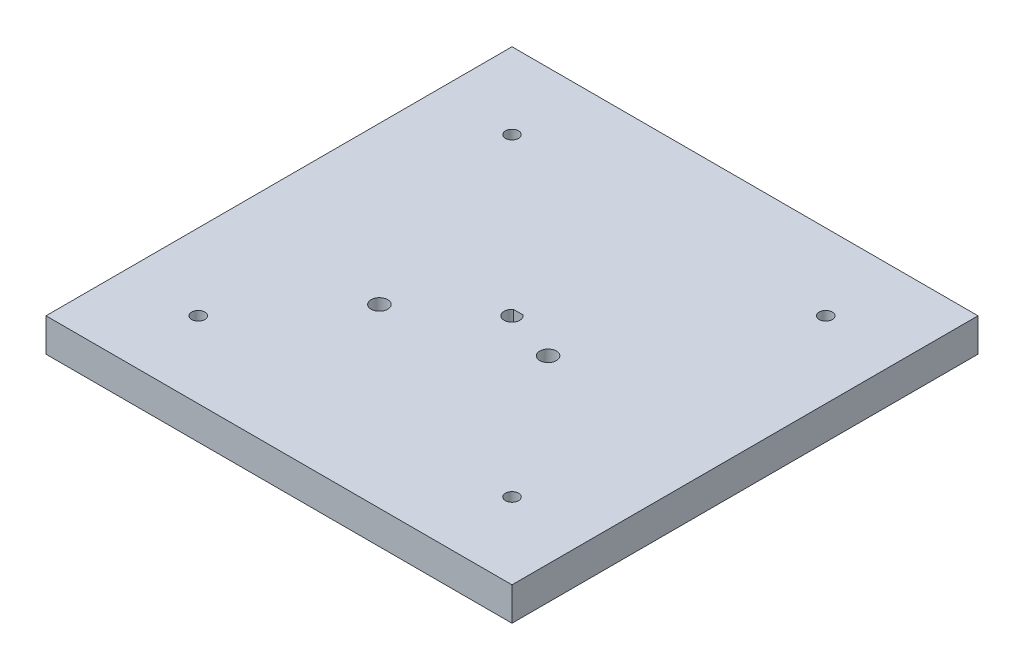
SolidWorks part; units mm, degrees
ref_plane "Front Plane" through (0, 0, 0) normal (0, 0, 1) x (1, 0, 0)
ref_plane "Top Plane" through (0, 0, 0) normal (0, 1, 0) x (1, 0, 0)
ref_plane "Right Plane" through (0, 0, 0) normal (1, 0, 0) x (0, 0, -1)
sketch "Sketch2" plane through (0, 0, 0) normal (0, 1, 0) x (1, 0, 0)
  line L0 (-1.8, 2.4) -> (1.8, 2.4)
  line L1 (-88.9, -88.9) -> (88.9, -88.9)
  line L2 (-88.9, -88.9) -> (-88.9, 88.9)
  line L3 (-88.9, 88.9) -> (88.9, 88.9)
  line L4 (88.9, -88.9) -> (88.9, 88.9)
  line L5 (-88.9, -88.9) -> (88.9, 88.9) construction
  line L6 (-88.9, 88.9) -> (88.9, -88.9) construction
  arc A1 (-1.8, 2.4) -> (1.8, 2.4) centre (0, 0) ccw
  arc A2 (1.8, 2.4) -> (-1.8, 2.4) centre (0, 0) ccw construction
  point P0 (0, 0)
  dimension "D3" = 6
  dimension "D1" = 177.8
  dimension "D2" = 177.8
  dimension "D4" = 2.4
extrude "Boss-Extrude1" add sketch "Sketch2" along normal mid plane 12.7
sketch "Sketch3" plane through (0, -6.35, 0) normal (0, -1, 0) x (1, 0, 0)
  circle A0 centre (-59.8566, -59.8566) radius 2.5 construction
  circle A1 centre (59.8566, -59.8566) radius 2.5 construction
  circle A2 centre (59.8566, 59.8566) radius 2.5 construction
  circle A3 centre (-59.8566, 59.8566) radius 2.5 construction
  circle A4 centre (-59.8566, -59.8566) radius 2.5
  circle A5 centre (59.8566, -59.8566) radius 2.5
  circle A6 centre (59.8566, 59.8566) radius 2.5
  circle A7 centre (-59.8566, 59.8566) radius 2.5
extrude "Cut-Extrude1" cut sketch "Sketch3" against normal up to surface (12.7 mm away) up to face at (0, 6.35, 0)
sketch "Sketch5" plane through (0, 6.35, 0) normal (0, 1, 0) x (1, 0, 0)
  circle A0 centre (20.1133, -6.35) radius 3.175 construction
  circle A1 centre (-29.0357, -21.5526) radius 3.175 construction
  circle A2 centre (20.1133, -6.35) radius 3.175
  circle A3 centre (-29.0357, -21.5526) radius 3.175
extrude "Cut-Extrude2" cut sketch "Sketch5" against normal up to next
